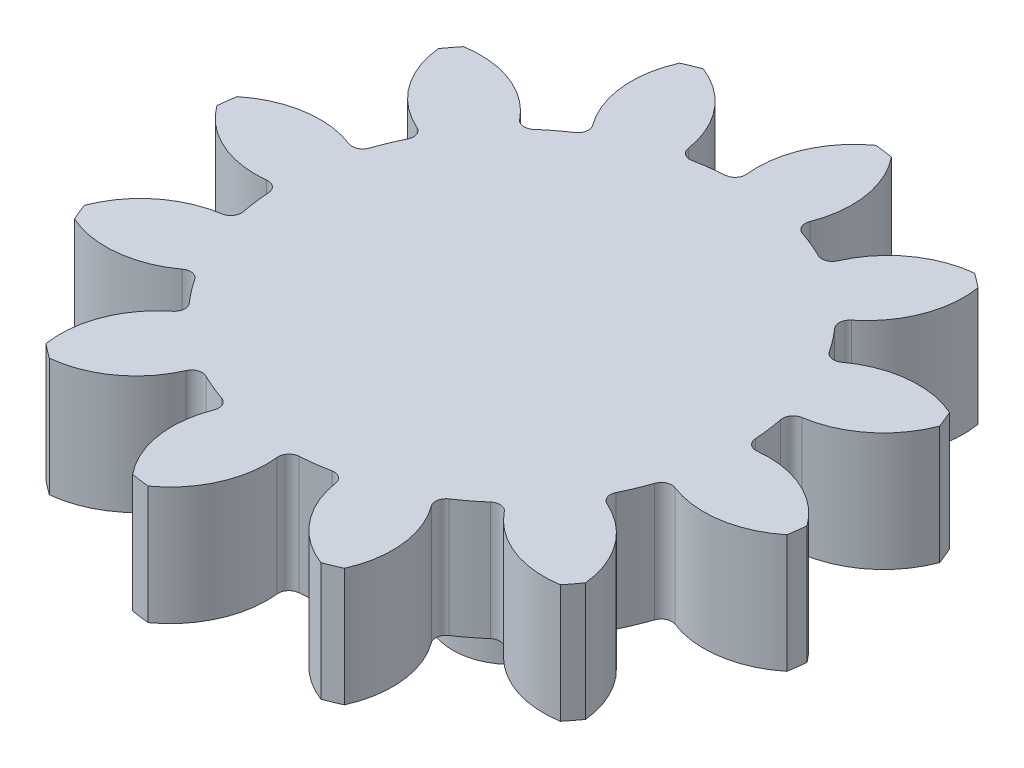
SolidWorks part; units mm, degrees
ref_plane "Alzado" through (0, 0, 0) normal (0, 0, 1) x (1, 0, 0)
ref_plane "Planta" through (0, 0, 0) normal (0, 1, 0) x (1, 0, 0)
ref_plane "Vista lateral" through (0, 0, 0) normal (1, 0, 0) x (0, 0, -1)
sketch "Croquis1" plane through (0, 0, 0) normal (0, 1, 0) x (1, 0, 0)
  line L0 (0, 0) -> (0, 33.4773) construction
  line L1 (0, 24) -> (7.7136, 21.1924) construction
  line L2 (0, 0) -> (4.4669, 33.831) construction
  line L3 (6.2291, 23.1775) -> (-1.9488, 22.4682) construction
  circle A0 centre (0, 0) radius 28 construction
  circle A1 centre (0, 0) radius 24 construction
  circle A2 centre (0, 0) radius 19.332 construction
  circle A3 centre (0, 0) radius 22.5526 construction
  arc A4 (2.9095, 27.8484) -> (-0.281, 19.33) centre (7.7136, 21.1924) ccw
  arc A5 (4.4182, 27.6492) -> (5.2884, 18.5946) centre (-1.9488, 22.4682) cw
  dimension "De" = 56
  dimension "Dp" = 48
  dimension "Di" = 38.664
  dimension "CT" = 45.1051
  dimension "D1" = 6.2832
sketch "Croquis2" plane through (0, 0, 0) normal (0, 1, 0) x (1, 0, 0)
  circle A0 centre (0, 0) radius 28 construction
  arc A1 (5.2884, 18.5946) -> (4.4182, 27.6492) centre (-1.9488, 22.4682) ccw construction
  arc A2 (2.9095, 27.8484) -> (-0.281, 19.33) centre (7.7136, 21.1924) ccw construction
  circle A3 centre (0, 0) radius 19.332 construction
  arc A4 (4.4182, 27.6492) -> (2.9095, 27.8484) centre (0, 0) ccw
  arc A5 (5.2884, 18.5946) -> (4.4182, 27.6492) centre (-1.9488, 22.4682) ccw
  arc A6 (2.9095, 27.8484) -> (-0.281, 19.33) centre (7.7136, 21.1924) ccw
  arc A7 (-0.281, 19.33) -> (5.2884, 18.5946) centre (0, 0) ccw
extrude "Saliente-Extruir1" add sketch "Croquis2" along normal blind 10
fillet "Redondeo1" radius 0.9 2 edges at (5.2884, 5, -18.5946) (-0.281, 5, -19.33)
pattern_circular "MatrizC3" count 12 over 360 about axis through (0, 0, 0) along (0, 1, 0) of "Saliente-Extruir1", "Redondeo1"
sketch "Croquis3" plane through (0, 0, 0) normal (0, -1, 0) x (1, 0, 0)
  circle A0 centre (0, 0) radius 5
  dimension "D1" = 10
extrude "Saliente-Extruir2" add sketch "Croquis3" along normal blind 12
sketch "Croquis4" plane through (0, -12, 0) normal (0, -1, 0) x (1, 0, 0)
  line L0 (0, 0) -> (0, 1.5) construction
  line L1 (-2.5764, 1.4875) -> (2.5764, 1.4875)
  arc A0 (-2.5764, 1.4875) -> (2.5764, 1.4875) centre (0, 0) ccw
  dimension "D1" = 5.95
  dimension "D2" = 1.5
extrude "Cortar-Extruir1" cut sketch "Croquis4" against normal blind 6.2
fillet "Redondeo2" radius 1 1 edges at (0, 0, 5)
equation "\"M\"= 4"
equation "\"N\"= 12"
equation "\"a\"= 20"
equation "\"De@Croquis1\"= \"M\" * ( \"N\" + 2 )"
equation "\"Dp@Croquis1\"= \"M\" * \"N\""
equation "\"Di@Croquis1\"= ( \"Dp@Croquis1\" ) - ( 2 * \"M\" * 1.167 )"
equation "\"CT@Croquis1\"= \"Dp@Croquis1\" * 0.93969"
equation "\"D1@Croquis1\"= \"M\" * 1.5708"
equation "\"D1@MatrizC3\"=\"N\""
